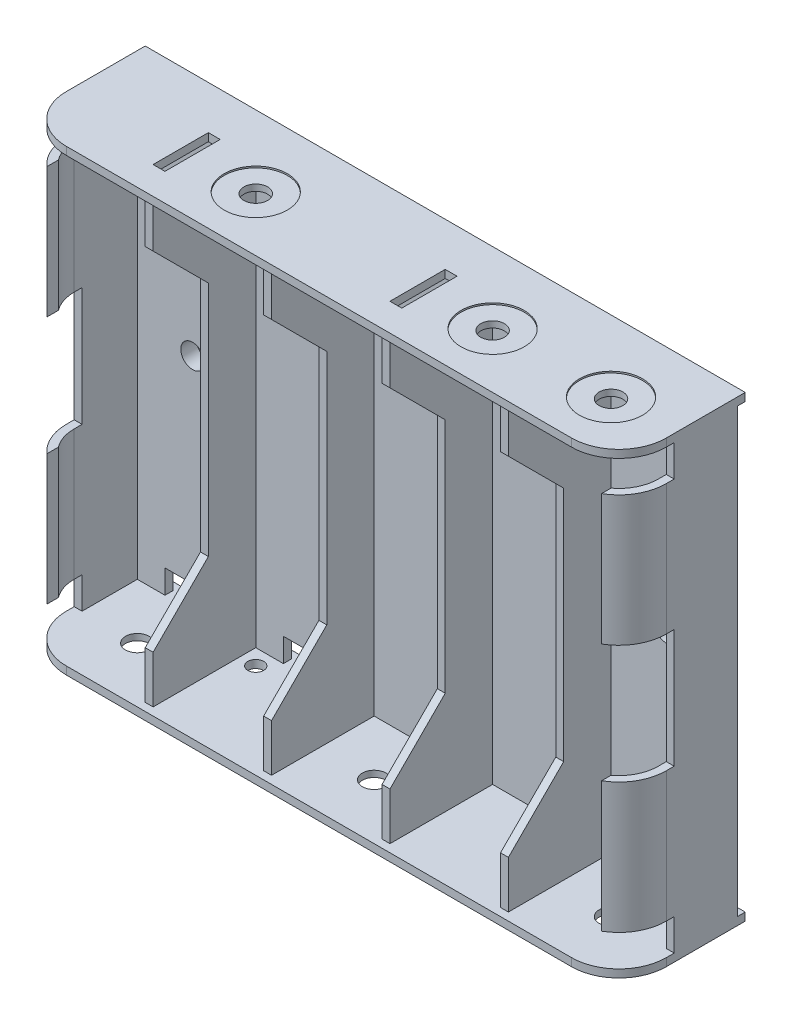
SolidWorks part; units mm, degrees
ref_plane "Plan de face" through (0, 0, 0) normal (0, 0, 1) x (1, 0, 0)
ref_plane "Plan de dessus" through (0, 0, 0) normal (0, 1, 0) x (1, 0, 0)
ref_plane "Plan de droite" through (0, 0, 0) normal (1, 0, 0) x (0, 0, -1)
sketch "Esquisse1" plane through (0, 0, 0) normal (0, 0, 1) x (1, 0, 0)
  line L1 (0, 0) -> (76, 0)
  line L2 (0, 0) -> (0, 58)
  line L3 (0, 58) -> (76, 58)
  line L4 (76, 0) -> (76, 58)
  dimension "D1" = 76
  dimension "D2" = 58
extrude "Boss.-Extru.1" add sketch "Esquisse1" along normal blind 2
sketch "Esquisse3" plane through (0, 0, 2) normal (0, 0, 1) x (1, 0, 0)
  line L0 (76, 58) -> (0, 58) construction
  line L1 (15, 58) -> (16, 58)
  line L2 (15, 58) -> (15, 0)
  line L3 (15, 0) -> (16, 0)
  line L4 (16, 58) -> (16, 0)
  line L5 (0, 0) -> (76, 0) construction
  line L6 (0, 58) -> (0, 0) construction
  dimension "D1" = 1
  dimension "D2" = 15
extrude "Boss.-Extru.2" add sketch "Esquisse3" along normal blind 13
sketch "Esquisse4" plane through (15, 0, 0) normal (-1, 0, 0) x (0, 0, 1)
  line L0 (15, 51) -> (8, 44)
  line L1 (15, 58) -> (15, 0) construction
  line L2 (8, 44) -> (8, 14)
  line L3 (8, 14) -> (15, 7)
  line L4 (15, 7) -> (15, 51)
  line L5 (15, 58) -> (2, 58) construction
  line L6 (15, 0) -> (2, 0) construction
  line L7 (2, 58) -> (2, 0) construction
  dimension "D1" = 7
  dimension "D2" = 7
  dimension "D3" = 7
  dimension "D4" = 7
  dimension "D5" = 6
extrude "Enlèv. mat.-Extru.2" cut sketch "Esquisse4" against normal up to next
sketch "Esquisse5" plane through (0, 0, 2) normal (0, 0, 1) x (1, 0, 0)
  line L0 (76, 58) -> (16, 58) construction
  line L1 (30, 58) -> (31, 58)
  line L2 (30, 58) -> (30, 0)
  line L3 (30, 0) -> (31, 0)
  line L4 (31, 58) -> (31, 0)
  line L5 (16, 0) -> (76, 0) construction
  line L6 (16, 14) -> (16, 44) construction
  dimension "D1" = 1
  dimension "D2" = 14
extrude "Boss.-Extru.3" add sketch "Esquisse5" along normal blind 13
sketch "Esquisse6" plane through (30, 0, 0) normal (-1, 0, 0) x (0, 0, 1)
  line L0 (15, 51) -> (8, 44)
  line L1 (8, 44) -> (8, 14)
  line L2 (8, 14) -> (15, 7)
  line L3 (15, 7) -> (15, 51)
extrude "Enlèv. mat.-Extru.3" cut sketch "Esquisse6" against normal up to next
sketch "Esquisse7" plane through (0, 0, 2) normal (0, 0, 1) x (1, 0, 0)
  line L0 (76, 58) -> (31, 58) construction
  line L1 (45, 58) -> (46, 58)
  line L2 (45, 58) -> (45, 0)
  line L3 (45, 0) -> (46, 0)
  line L4 (46, 58) -> (46, 0)
  line L5 (31, 0) -> (76, 0) construction
  line L6 (31, 14) -> (31, 44) construction
  dimension "D1" = 1
  dimension "D2" = 14
extrude "Boss.-Extru.4" add sketch "Esquisse7" along normal blind 13
sketch "Esquisse8" plane through (45, 0, 0) normal (-1, 0, 0) x (0, 0, 1)
  line L0 (15, 51) -> (8, 44)
  line L1 (8, 44) -> (8, 14)
  line L2 (8, 14) -> (15, 7)
  line L3 (15, 7) -> (15, 51)
extrude "Enlèv. mat.-Extru.4" cut sketch "Esquisse8" against normal up to next
sketch "Esquisse9" plane through (0, 0, 2) normal (0, 0, 1) x (1, 0, 0)
  line L0 (76, 58) -> (46, 58) construction
  line L1 (60, 58) -> (61, 58)
  line L2 (60, 58) -> (60, 0)
  line L3 (60, 0) -> (61, 0)
  line L4 (61, 58) -> (61, 0)
  line L5 (46, 0) -> (76, 0) construction
  line L6 (46, 0) -> (46, 58) construction
  dimension "D1" = 1
  dimension "D2" = 14
extrude "Boss.-Extru.5" add sketch "Esquisse9" along normal blind 13
sketch "Esquisse10" plane through (60, 0, 0) normal (-1, 0, 0) x (0, 0, 1)
  line L0 (15, 51) -> (8, 44)
  line L1 (8, 44) -> (8, 14)
  line L2 (8, 14) -> (15, 7) construction
  line L3 (8, 44) -> (8, 14) construction
  line L4 (8, 14) -> (15, 7)
  line L5 (15, 7) -> (15, 51)
extrude "Enlèv. mat.-Extru.5" cut sketch "Esquisse10" against normal up to next
sketch "Esquisse11" plane through (0, 0, 2) normal (0, 0, 1) x (1, 0, 0)
  line L0 (76, 0) -> (76, 58) construction
  line L1 (0, 0) -> (76, 0)
  line L2 (0, 0) -> (0, 1)
  line L3 (0, 1) -> (76, 1)
  line L4 (76, 0) -> (76, 1)
  dimension "D1" = 1
extrude "Boss.-Extru.6" add sketch "Esquisse11" along normal blind 14
sketch "Esquisse12" plane through (0, 0, 2) normal (0, 0, 1) x (1, 0, 0)
  line L0 (76, 1) -> (76, 58) construction
  line L1 (0, 58) -> (76, 58)
  line L2 (0, 58) -> (0, 57)
  line L3 (0, 57) -> (76, 57)
  line L4 (76, 58) -> (76, 57)
  dimension "D1" = 1
extrude "Boss.-Extru.7" add sketch "Esquisse12" along normal blind 14
sketch "Esquisse13" plane through (0, 0, 0) normal (0, -1, 0) x (1, 0, 0)
  line L0 (76, 16) -> (76, 0) construction
  line L1 (0, 16) -> (76, 16) construction
  line L2 (70, 16) -> (76, 16)
  line L3 (76, 16) -> (76, 10)
  arc A0 (70, 16) -> (76, 10) centre (70, 10) cw
  dimension "D3" = 6
  dimension "D1" = 6
  dimension "D2" = 6
extrude "Enlèv. mat.-Extru.6" cut sketch "Esquisse13" against normal up to next
sketch "Esquisse14" plane through (0, 0, 0) normal (0, -1, 0) x (1, 0, 0)
  line L0 (0, 16) -> (0, 0) construction
  line L1 (0, 16) -> (70, 16) construction
  line L2 (6, 16) -> (0, 16)
  line L3 (0, 16) -> (0, 10)
  arc A0 (0, 10) -> (6, 16) centre (6, 10) cw
  dimension "D2" = 6
  dimension "D1" = 6
  dimension "D3" = 6
extrude "Enlèv. mat.-Extru.7" cut sketch "Esquisse14" against normal up to next
sketch "Esquisse15" plane through (0, 58, 0) normal (0, 1, 0) x (1, 0, 0)
  line L0 (0, -16) -> (0, 0) construction
  line L1 (76, -16) -> (0, -16) construction
  line L2 (0, -10) -> (0, -16)
  line L3 (6, -16) -> (0, -16)
  arc A0 (0, -10) -> (6, -16) centre (6, -10) ccw
  dimension "D1" = 6
  dimension "D2" = 6
  dimension "D3" = 6
extrude "Enlèv. mat.-Extru.8" cut sketch "Esquisse15" against normal up to next
sketch "Esquisse17" plane through (0, 58, 0) normal (0, 1, 0) x (1, 0, 0)
  line L0 (76, -16) -> (6, -16) construction
  line L1 (76, -16) -> (76, 0) construction
  line L2 (70, -16) -> (76, -16)
  line L3 (76, -16) -> (76, -10)
  arc A0 (76, -10) -> (70, -16) centre (70, -10) cw
  dimension "D1" = 6
  dimension "D2" = 6
  dimension "D3" = 6
extrude "Enlèv. mat.-Extru.9" cut sketch "Esquisse17" against normal up to next
sketch "Esquisse18" plane through (0, 0, 0) normal (0, 0, -1) x (-1, 0, 0)
  line L0 (-76, 0) -> (-76, 58) construction
  line L1 (-76, 57) -> (0, 57)
  line L2 (-76, 57) -> (-76, 1)
  line L3 (-76, 1) -> (0, 1)
  line L4 (0, 57) -> (0, 1)
  line L5 (0, 58) -> (0, 0) construction
  line L6 (-76, 58) -> (0, 58) construction
  line L7 (0, 0) -> (-76, 0) construction
  dimension "D1" = 1
  dimension "D2" = 1
extrude "Enlèv. mat.-Extru.10" cut sketch "Esquisse18" against normal blind 1
sketch "Esquisse19" plane through (0, 0, 2) normal (0, 0, 1) x (1, 0, 0)
  line L0 (76, 1) -> (61, 1) construction
  line L1 (76, 57) -> (75, 57)
  line L2 (76, 57) -> (76, 1)
  line L3 (76, 1) -> (75, 1)
  line L4 (75, 57) -> (75, 1)
  dimension "D1" = 1
extrude "Boss.-Extru.8" add sketch "Esquisse19" along normal blind 8 contours L4 L3 L2 L1
sketch "Esquisse20" plane through (0, 0, 2) normal (0, 0, 1) x (1, 0, 0)
  line L0 (15, 1) -> (0, 1) construction
  line L1 (0, 57) -> (1, 57)
  line L2 (0, 57) -> (0, 1)
  line L3 (0, 1) -> (1, 1)
  line L4 (1, 57) -> (1, 1)
  dimension "D1" = 1
extrude "Boss.-Extru.9" add sketch "Esquisse20" along normal blind 8 contours L4 L3 L2 L1
sketch "Esquisse21" plane through (0, 57, 0) normal (0, -1, 0) x (1, 0, 0)
  line L5 (6, 15) -> (6, 16)
  line L6 (1, 10) -> (0, 10)
  arc A0 (6, 16) -> (0, 10) centre (6, 10) ccw
  arc A2 (6, 15) -> (1, 10) centre (6, 10) ccw
  dimension "D1" = 1
extrude "Boss.-Extru.10" add sketch "Esquisse21" along normal up to next
sketch "Esquisse22" plane through (0, 1, 0) normal (0, 1, 0) x (1, 0, 0)
  line L0 (70, -16) -> (70, -15)
  line L1 (76, -10) -> (75, -10)
  arc A0 (76, -10) -> (70, -16) centre (70, -10) cw
  arc A1 (75, -10) -> (70, -15) centre (70, -10) cw
  dimension "D1" = 1
extrude "Boss.-Extru.11" add sketch "Esquisse22" along normal up to next contours A1 L0 A0 L1
sketch "Esquisse23" plane through (0, 0, 16) normal (0, 0, 1) x (1, 0, 0)
  line L1 (69, 57) -> (73, 57)
  line L2 (69, 57) -> (69, 1)
  line L3 (69, 1) -> (73, 1)
  line L4 (73, 57) -> (73, 1)
  line L6 (70, 1) -> (6, 1) construction
  line L7 (61, 51) -> (61, 57) construction
  line L8 (6, 57) -> (70, 57) construction
  point P10 (71, 57)
  dimension "D1" = 4
  dimension "D2" = 12
  dimension "D3" = 0
  dimension "D4" = 0
extrude "Enlèv. mat.-Extru.11" cut sketch "Esquisse23" against normal blind 5 contours L4 L3 L2 L1
sketch "Esquisse24" plane through (0, 0, 16) normal (0, 0, 1) x (1, 0, 0)
  line L0 (15, 1) -> (1, 1) construction
  line L1 (6, 57) -> (2, 57)
  line L2 (6, 57) -> (6, 1)
  line L3 (6, 1) -> (2, 1)
  line L4 (2, 57) -> (2, 1)
  dimension "D1" = 4
extrude "Enlèv. mat.-Extru.12" cut sketch "Esquisse24" against normal blind 5
sketch "Esquisse25" plane through (0, 0, 0) normal (-1, 0, 0) x (0, 0, 1)
  line L0 (14.4721, 1) -> (14.4721, 57) construction
  line L1 (14.4721, 57) -> (9, 57)
  line L2 (14.4721, 57) -> (14.4721, 53)
  line L3 (14.4721, 53) -> (9, 53)
  line L4 (9, 57) -> (9, 53)
  line L5 (14.4721, 36.5) -> (9, 36.5)
  line L6 (14.4721, 36.5) -> (14.4721, 21.5)
  line L7 (14.4721, 21.5) -> (9, 21.5)
  line L8 (9, 36.5) -> (9, 21.5)
  line L9 (1, 1) -> (1, 57) construction
  line L10 (14.4721, 1) -> (9, 1)
  line L11 (14.4721, 1) -> (14.4721, 5)
  line L12 (14.4721, 5) -> (9, 5)
  line L13 (9, 1) -> (9, 5)
  line L14 (10, 0) -> (16, 0) construction
  dimension "D1" = 8
  dimension "D2" = 8
  dimension "D3" = 8
  dimension "D4" = 15
  dimension "D5" = 4
  dimension "D6" = 4
  dimension "D7" = 21.5
extrude "Enlèv. mat.-Extru.13" cut sketch "Esquisse25" against normal blind 5
sketch "Esquisse26" plane through (76, 0, 0) normal (1, 0, 0) x (0, 0, -1)
  line L0 (-15.1962, 1) -> (-15.1962, 57) construction
  line L1 (-15.1962, 57) -> (-9, 57)
  line L2 (-15.1962, 57) -> (-15.1962, 53)
  line L3 (-15.1962, 53) -> (-9, 53)
  line L4 (-9, 57) -> (-9, 53)
  line L5 (-15.1962, 36.5) -> (-9, 36.5)
  line L6 (-15.1962, 36.5) -> (-15.1962, 21.5)
  line L7 (-15.1962, 21.5) -> (-9, 21.5)
  line L8 (-9, 36.5) -> (-9, 21.5)
  line L9 (-10, 0) -> (0, 0) construction
  line L10 (-15.1962, 1) -> (-9, 1)
  line L11 (-15.1962, 1) -> (-15.1962, 5)
  line L12 (-15.1962, 5) -> (-9, 5)
  line L13 (-9, 1) -> (-9, 5)
  line L14 (-1, 57) -> (-1, 1) construction
  dimension "D1" = 4
  dimension "D2" = 4
  dimension "D3" = 15
  dimension "D4" = 21.5
  dimension "D5" = 8
  dimension "D6" = 8
  dimension "D7" = 8
extrude "Enlèv. mat.-Extru.14" cut sketch "Esquisse26" against normal blind 5
sketch "Esquisse27" plane through (0, 0, 1) normal (0, 0, -1) x (-1, 0, 0)
  line L0 (-76, 57) -> (-76, 1) construction
  line L1 (0, 0) -> (-76, 0) construction
  circle A0 centre (-68, 29) radius 1.5
  circle A1 centre (-8, 29) radius 1.5
  dimension "D1" = 3
  dimension "D2" = 3
  dimension "D3" = 60
  dimension "D4" = 8
  dimension "D5" = 29
  dimension "D6" = 29
extrude "Enlèv. mat.-Extru.15" cut sketch "Esquisse27" against normal up to next
sketch "Esquisse28" plane through (0, 0, 1) normal (0, 0, -1) x (-1, 0, 0)
  circle A0 centre (-68, 29) radius 2.5
  circle A1 centre (-8, 29) radius 2.5
  dimension "D1" = 5
  dimension "D2" = 5
extrude "Boss.-Extru.12" add sketch "Esquisse28" along normal blind 1
sketch "Esquisse29" plane through (0, 0, 0) normal (0, 0, -1) x (-1, 0, 0)
  circle A0 centre (-68, 29) radius 1.5
  circle A1 centre (-8, 29) radius 1.5
  dimension "D1" = 3
  dimension "D2" = 3
extrude "Enlèv. mat.-Extru.16" cut sketch "Esquisse29" against normal up to next
sketch "Esquisse30" plane through (0, 0, 1) normal (0, 0, -1) x (-1, 0, 0)
  line L0 (0, 57) -> (-76, 57) construction
  line L1 (-71.5, 57) -> (-64.5, 57)
  line L2 (-71.5, 57) -> (-71.5, 54)
  line L3 (-71.5, 54) -> (-64.5, 54)
  line L4 (-64.5, 57) -> (-64.5, 54)
  line L5 (-76, 57) -> (-76, 1) construction
  line L6 (-76, 1) -> (0, 1) construction
  line L7 (-4.5, 1) -> (-11.5, 1)
  line L8 (-4.5, 1) -> (-4.5, 4)
  line L9 (-4.5, 4) -> (-11.5, 4)
  line L10 (-11.5, 1) -> (-11.5, 4)
  line L11 (0, 1) -> (0, 57) construction
  line L13 (-19.5, 1) -> (-26.5, 1)
  line L14 (-19.5, 1) -> (-19.5, 4)
  line L15 (-19.5, 4) -> (-26.5, 4)
  line L16 (-26.5, 1) -> (-26.5, 4)
  point P20 (-11.5, 2.5)
  dimension "D1" = 4.5
  dimension "D2" = 7
  dimension "D3" = 3
  dimension "D4" = 4.5
  dimension "D5" = 7
  dimension "D6" = 3
  dimension "D7" = 7
  dimension "D8" = 3
  dimension "D9" = 8
extrude "Enlèv. mat.-Extru.17" cut sketch "Esquisse30" against normal up to next
sketch "Esquisse31" plane through (0, 0, 1) normal (0, 0, -1) x (-1, 0, 0)
  line L0 (-21, 4) -> (-66, 54)
  line L1 (-19.5, 4) -> (-26.5, 4) construction
  line L2 (-71.5, 54) -> (-64.5, 54) construction
  line L3 (-76, 57) -> (-76, 1) construction
  line L4 (-19.5, 1) -> (-19.5, 4) construction
  line L5 (-22.3454, 4) -> (-67.3454, 54)
  line L6 (-21.7433, 3.331) -> (-66.7433, 53.331) construction
  line L7 (-23.6907, 4) -> (-68.6907, 54)
  line L8 (-22.4866, 2.6621) -> (-68.0887, 53.331) construction
  line L9 (-19.6546, 4) -> (-64.6546, 54)
  line L10 (-22.3454, 4) -> (-23.6907, 4)
  line L11 (-66, 54) -> (-64.6546, 54)
  line L12 (-21.7433, 3.331) -> (-67.3454, 54) construction
  line L13 (-67.3454, 54) -> (-68.6907, 54)
  line L14 (-20.2567, 4.669) -> (-65.2567, 54.669) construction
  line L15 (-19.6546, 4) -> (-21, 4)
  dimension "D1" = 10
  dimension "D2" = 1.5
  dimension "D3" = 1
  dimension "D4" = 1
  dimension "D5" = 1
extrude "Boss.-Extru.13" add sketch "Esquisse31" along normal blind 1
sketch "Esquisse32" plane through (0, 0, 0) normal (0, -1, 0) x (1, 0, 0)
  line L0 (0, 10) -> (0, 0) construction
  line L1 (0, 0) -> (76, 0) construction
  circle A0 centre (14, 4) radius 1
  circle A1 centre (18, 4) radius 1
  dimension "D2" = 2
  dimension "D5" = 2
  dimension "D1" = 14
  dimension "D3" = 4
  dimension "D4" = 4
  dimension "D6" = 4
extrude "Enlèv. mat.-Extru.18" cut sketch "Esquisse32" against normal up to next
sketch "Esquisse33" plane through (0, 58, 0) normal (0, 1, 0) x (1, 0, 0)
  line L0 (76, 0) -> (0, 0) construction
  line L1 (76, -10) -> (76, 0) construction
  circle A0 centre (68, -9) radius 4
  circle A1 centre (53, -9) radius 4
  circle A2 centre (23, -9) radius 4
  dimension "D1" = 8
  dimension "D4" = 8
  dimension "D9" = 8
  dimension "D2" = 9
  dimension "D3" = 8
  dimension "D5" = 15
  dimension "D6" = 30
  dimension "D7" = 9
  dimension "D8" = 9
extrude "Enlèv. mat.-Extru.19" cut sketch "Esquisse33" against normal blind 0.2
sketch "Esquisse34" plane through (0, 0, 0) normal (0, -1, 0) x (1, 0, 0)
  line L0 (0, 10) -> (0, 0) construction
  line L1 (0, 0) -> (76, 0) construction
  circle A0 centre (8, 9) radius 4
  circle A1 centre (38, 9) radius 4
  circle A2 centre (68, 9) radius 4
  dimension "D3" = 8
  dimension "D5" = 8
  dimension "D8" = 8
  dimension "D1" = 8
  dimension "D2" = 9
  dimension "D4" = 9
  dimension "D6" = 30
  dimension "D7" = 30
  dimension "D9" = 9
extrude "Enlèv. mat.-Extru.20" cut sketch "Esquisse34" against normal blind 0.2
sketch "Esquisse35" plane through (0, 0.2, 0) normal (0, -1, 0) x (1, 0, 0)
  circle A0 centre (38, 9) radius 1.5
  circle A1 centre (68, 9) radius 1.5
  circle A2 centre (8, 9) radius 1.5
  dimension "D1" = 3
  dimension "D2" = 3
  dimension "D3" = 3
extrude "Enlèv. mat.-Extru.21" cut sketch "Esquisse35" against normal up to next
sketch "Esquisse36" plane through (0, 57.8, 0) normal (0, 1, 0) x (1, 0, 0)
  circle A0 centre (68, -9) radius 1.5
  circle A1 centre (53, -9) radius 1.5
  circle A2 centre (23, -9) radius 1.5
  dimension "D1" = 3
  dimension "D2" = 3
  dimension "D3" = 3
extrude "Enlèv. mat.-Extru.22" cut sketch "Esquisse36" against normal up to next
sketch "Esquisse37" plane through (0, 0, 0) normal (0, -1, 0) x (1, 0, 0)
  line L0 (0, 0) -> (76, 0) construction
  line L1 (58, 12.5) -> (60, 12.5)
  line L2 (58, 12.5) -> (58, 5.5)
  line L3 (58, 5.5) -> (60, 5.5)
  line L4 (60, 12.5) -> (60, 5.5)
  line L5 (28, 12.5) -> (30, 12.5)
  line L6 (28, 12.5) -> (28, 5.5)
  line L7 (28, 5.5) -> (30, 5.5)
  line L8 (30, 12.5) -> (30, 5.5)
  line L9 (76, 10) -> (76, 0) construction
  dimension "D1" = 2
  dimension "D2" = 2
  dimension "D3" = 7
  dimension "D4" = 7
  dimension "D5" = 5.5
  dimension "D6" = 5.5
  dimension "D7" = 46
  dimension "D8" = 16
extrude "Enlèv. mat.-Extru.23" cut sketch "Esquisse37" against normal up to next
sketch "Esquisse38" plane through (0, 58, 0) normal (0, 1, 0) x (1, 0, 0)
  line L0 (76, 0) -> (0, 0) construction
  line L1 (43.5, -5.5032) -> (45, -5.5032)
  line L2 (43.5, -5.5032) -> (43.5, -12.5032)
  line L3 (43.5, -12.5032) -> (45, -12.5032)
  line L4 (45, -5.5032) -> (45, -12.5032)
  line L5 (15, -5.5032) -> (13.5, -5.5032)
  line L6 (15, -5.5032) -> (15, -12.5032)
  line L7 (15, -12.5032) -> (13.5, -12.5032)
  line L8 (13.5, -5.5032) -> (13.5, -12.5032)
  line L9 (0, -10) -> (0, 0) construction
  dimension "D1" = 1.5
  dimension "D2" = 1.5
  dimension "D3" = 7
  dimension "D4" = 7
  dimension "D5" = 5.5032
  dimension "D6" = 5.5032
  dimension "D7" = 13.5
  dimension "D8" = 43.5
extrude "Enlèv. mat.-Extru.24" cut sketch "Esquisse38" against normal up to next
